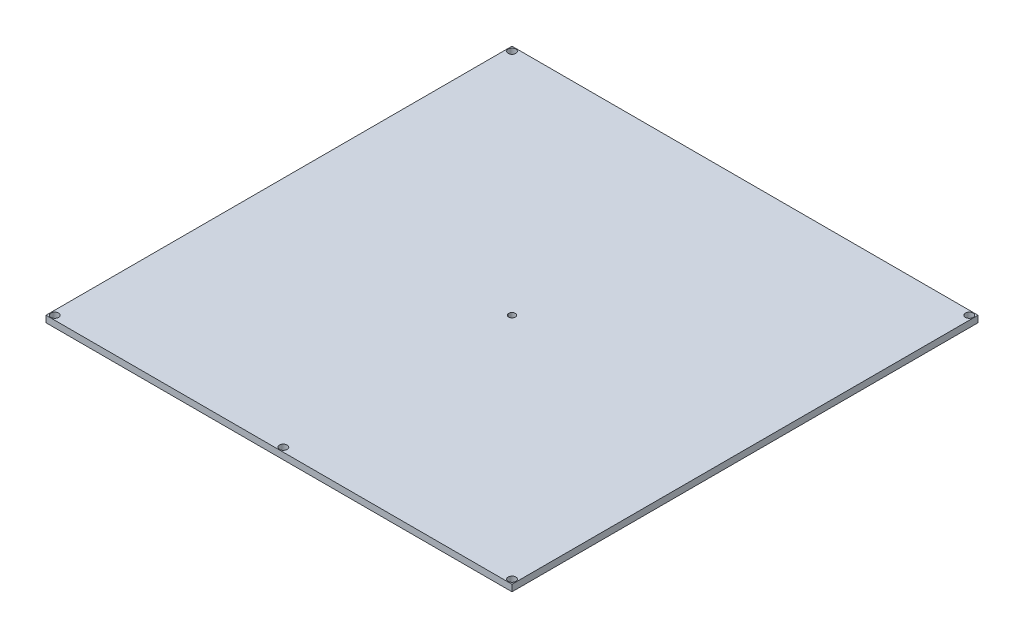
SolidWorks part; units mm, degrees
ref_plane "Front Plane" through (0, 0, 0) normal (0, 0, 1) x (1, 0, 0)
ref_plane "Top Plane" through (0, 0, 0) normal (0, 1, 0) x (1, 0, 0)
ref_plane "Right Plane" through (0, 0, 0) normal (1, 0, 0) x (0, 0, -1)
sketch "Sketch1" plane through (0, 0, 0) normal (0, 1, 0) x (1, 0, 0)
  line L0 (-104.5, -104.5) -> (104.5, -104.5) construction
  line L1 (-106.5, -106.5) -> (106.5, -106.5)
  line L2 (-106.5, -106.5) -> (-106.5, 106.5)
  line L3 (-106.5, 106.5) -> (106.5, 106.5)
  line L4 (106.5, -106.5) -> (106.5, 106.5)
  line L5 (-106.5, -106.5) -> (106.5, 106.5) construction
  line L6 (-106.5, 106.5) -> (106.5, -106.5) construction
  line L7 (-104.5, -104.5) -> (104.5, -104.5) construction
  line L8 (-104.5, -104.5) -> (-104.5, 104.5) construction
  line L9 (-104.5, 104.5) -> (104.5, 104.5) construction
  line L10 (104.5, -104.5) -> (104.5, 104.5) construction
  line L11 (-104.5, -104.5) -> (104.5, 104.5) construction
  line L12 (-104.5, 104.5) -> (104.5, -104.5) construction
  line L13 (0, 0) -> (0, -104.5) construction
  circle A0 centre (-104.5, 104.5) radius 1.75
  circle A1 centre (104.5, 104.5) radius 1.75
  circle A2 centre (-104.5, -104.5) radius 1.75
  circle A3 centre (104.5, -104.5) radius 1.75
  circle A4 centre (0, -104.5) radius 1.75
  circle A5 centre (0, 0) radius 1.5
  point P0 (0, 0)
  point P6 (0, 0)
  dimension "D3" = 3.5
  dimension "D5" = 2
  dimension "D6" = 3.5
  dimension "D7" = 3
  dimension "D1" = 213
  dimension "D2" = 209
  dimension "D4" = 2
extrude "Boss-Extrude1" add sketch "Sketch1" along normal blind 3
